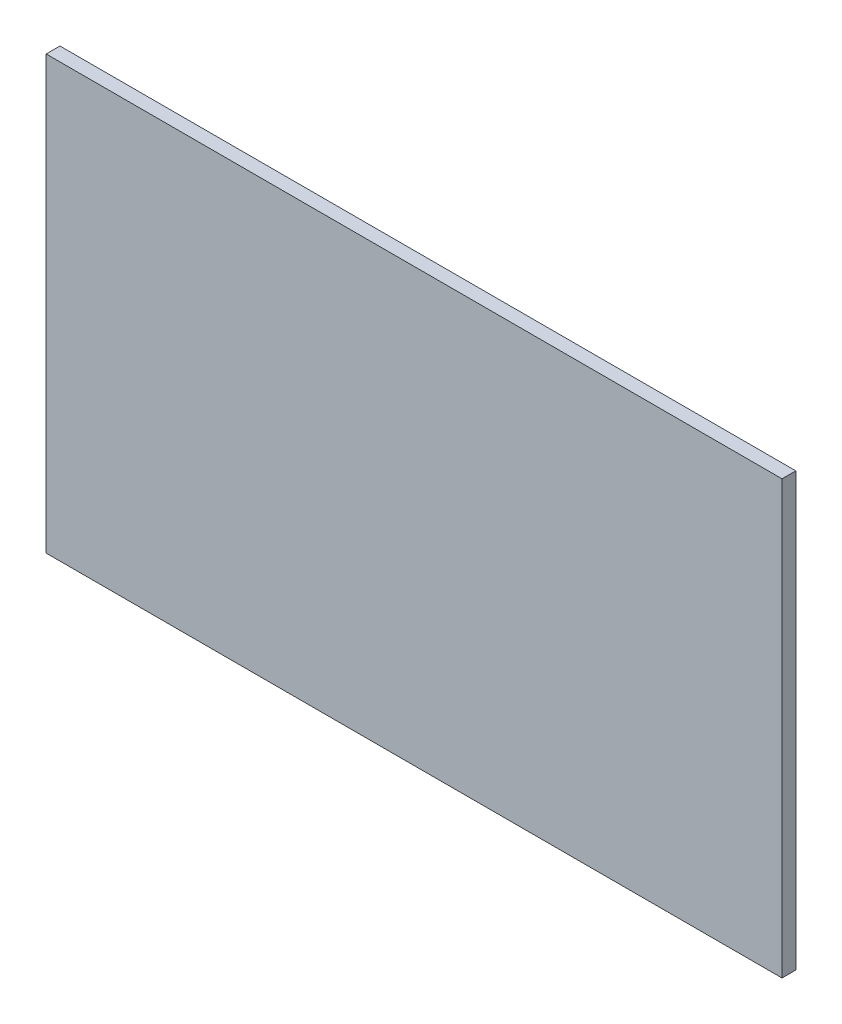
SolidWorks part; units mm, degrees
material "Glass"
ref_plane "Front Plane" through (0, 0, 0) normal (0, 0, 1) x (1, 0, 0)
ref_plane "Top Plane" through (0, 0, 0) normal (0, 1, 0) x (1, 0, 0)
ref_plane "Right Plane" through (0, 0, 0) normal (1, 0, 0) x (0, 0, -1)
sketch "Sketch1" plane through (0, 0, 0) normal (0, 0, 1) x (1, 0, 0)
  line L0 (-80, 0) -> (80, 0)
  line L1 (-80, 0) -> (-80, -94)
  line L3 (80, 0) -> (80, -94)
  line L4 (-80, -94) -> (80, -94)
  point P1 (0, 0)
  point P6 (-61.4445, -124.6098)
  point P7 (61.4445, -124.6098)
  dimension "D1" = 94
  dimension "D2" = 160
extrude "Boss-Extrude1" add sketch "Sketch1" along normal mid plane 3
